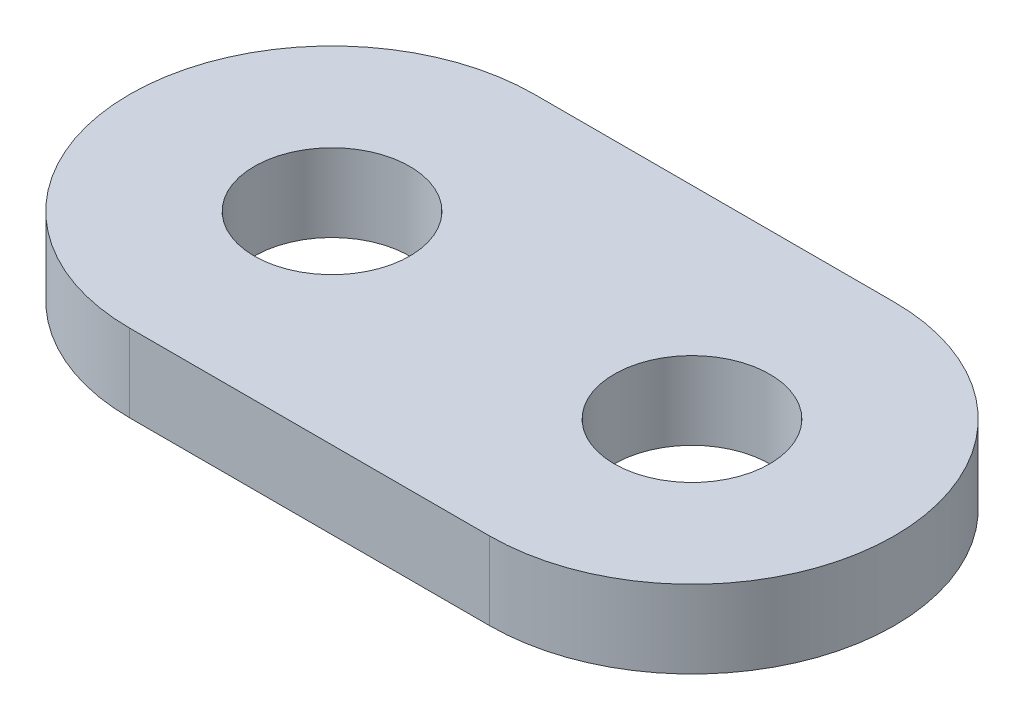
SolidWorks part; units mm, degrees
material "6061-T6 (SS)"
ref_plane "Front Plane" through (0, 0, 0) normal (0, 0, 1) x (1, 0, 0)
ref_plane "Top Plane" through (0, 0, 0) normal (0, 1, 0) x (1, 0, 0)
ref_plane "Right Plane" through (0, 0, 0) normal (1, 0, 0) x (0, 0, -1)
sketch "Sketch1" plane through (0, 0, 0) normal (0, 1, 0) x (1, 0, 0)
  line L0 (-3.675, 0) -> (3.675, 0) construction
  line L1 (3.675, 4.1337) -> (-3.675, 4.1337)
  line L3 (-3.675, -4.1337) -> (3.675, -4.1337)
  line L6 (3.675, 1.6337) -> (-3.675, 1.6337) construction
  line L7 (-3.675, -1.6337) -> (3.675, -1.6337) construction
  circle A0 centre (3.675, 0) radius 1.5875
  circle A1 centre (-3.675, 0) radius 1.5875
  arc A2 (-3.675, 4.1337) -> (-3.675, -4.1337) centre (-3.675, 0) ccw
  arc A3 (3.675, -4.1337) -> (3.675, 4.1337) centre (3.675, 0) ccw
  circle A4 centre (-9.4564, 0) radius 0.5953 construction
  circle A5 centre (-4.9564, 0) radius 0.5953 construction
  arc A7 (3.675, -1.6337) -> (3.675, 1.6337) centre (3.675, 0) ccw
  arc A8 (-3.675, 1.6337) -> (-3.675, -1.6337) centre (-3.675, 0) ccw construction
  point P3 (0, 0)
  dimension "D2" = 3.175
  dimension "D3" = 1.1906
  dimension "D4" = 4.5
  dimension "D1" = 7.35
  dimension "D5" = 2.5
extrude "Boss-Extrude2" add sketch "Sketch1" along normal mid plane 1.5875
